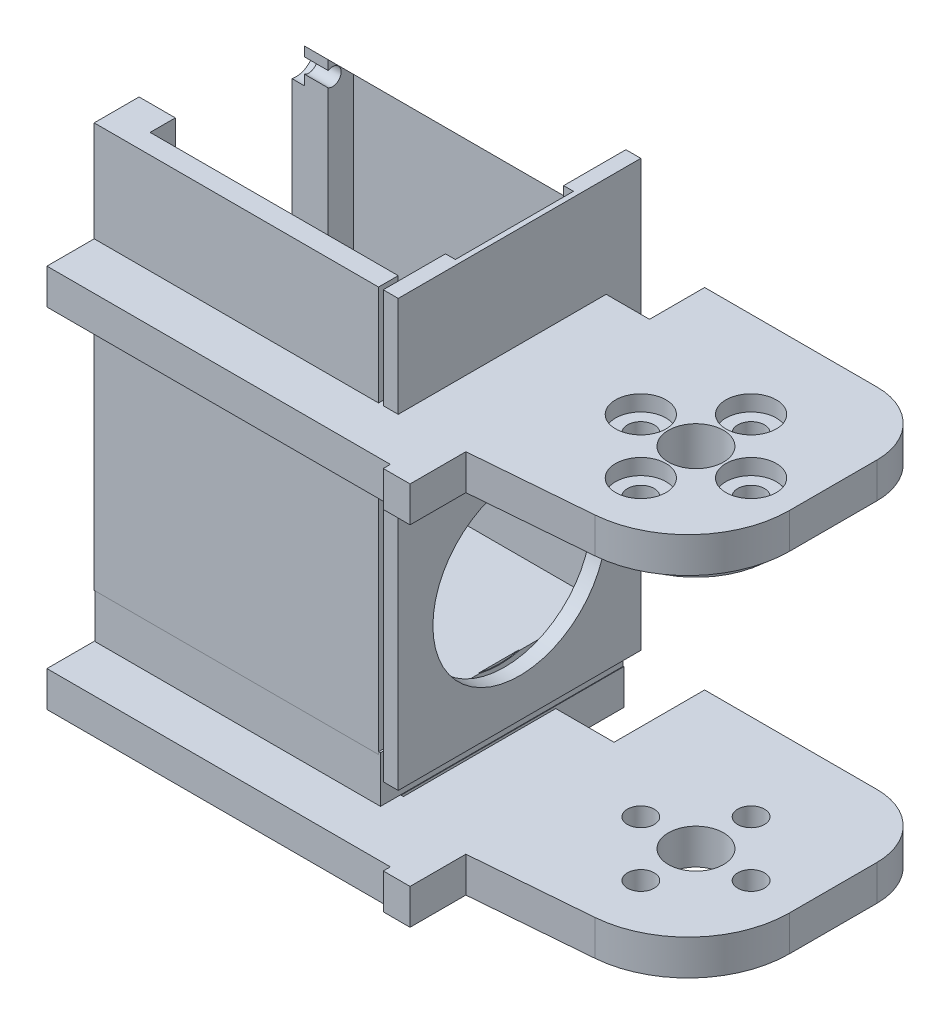
SolidWorks part; units mm, degrees
ref_plane "Front Plane" through (0, 0, 0) normal (0, 0, 1) x (1, 0, 0)
ref_plane "Top Plane" through (0, 0, 0) normal (0, 1, 0) x (1, 0, 0)
ref_plane "Right Plane" through (0, 0, 0) normal (1, 0, 0) x (0, 0, -1)
ref_plane "PY_m23_300" through (0, -23.3, 0) normal (0, 1, 0) x (1, 0, 0)
sketch "S_prism1" plane through (0, -23.3, 0) normal (0, 1, 0) x (1, 0, 0)
  line L0 (13, 10) -> (13, -1.1138)
  line L1 (1.1535, -13.9707) -> (-16.9, -15.45)
  line L2 (-16.9, -15.45) -> (-16.9, 18)
  line L3 (-16.9, 18) -> (5, 18)
  arc A0 (5, 18) -> (13, 10) centre (5.0002, 10.0002) cw
  arc A1 (13, -1.1138) -> (1.1535, -13.9707) centre (0.1, -1.1138) cw
extrude "Boss_1" add sketch "S_prism1" along normal blind 4.5
ref_plane "PY_p17_750" through (0, 17.75, 0) normal (0, 1, 0) x (1, 0, 0)
sketch "S_cyl2" plane through (0, 17.75, 0) normal (0, 1, 0) x (1, 0, 0)
  circle A0 centre (0, 0) radius 9.5
  dimension "D1_S_cyl2" = 19
extrude "Boss_2" add sketch "S_cyl2" along normal blind 3.2
ref_plane "PY_p20_950" through (0, 20.95, 0) normal (0, 1, 0) x (1, 0, 0)
sketch "S_prism3" plane through (0, 20.95, 0) normal (0, 1, 0) x (1, 0, 0)
  line L0 (13, 10) -> (13, -1.1138)
  line L1 (1.1535, -13.9707) -> (-16.9, -15.45)
  line L2 (-16.9, -15.45) -> (-16.9, 18)
  line L3 (-16.9, 18) -> (5, 18)
  arc A0 (5, 18) -> (13, 10) centre (5.0002, 10.0002) cw
  arc A1 (13, -1.1138) -> (1.1535, -13.9707) centre (0.1, -1.1138) cw
extrude "Boss_3" add sketch "S_prism3" along normal blind 4.5
sketch "S_prism4" plane through (0, -23.3, 0) normal (0, 1, 0) x (1, 0, 0)
  line L0 (-24.3, 6.5) -> (-16.8, 6.5)
  line L1 (-16.8, 6.5) -> (-16.8, -15.45)
  line L2 (-16.8, -15.45) -> (-24.3, -15.45)
  line L3 (-24.3, -15.45) -> (-24.3, 6.5)
extrude "Boss_4" add sketch "S_prism4" along normal blind 4.5
sketch "S_prism5" plane through (0, -23.3, 0) normal (0, 1, 0) x (1, 0, 0)
  line L0 (-61, -12.85) -> (-16.8, -12.85)
  line L1 (-16.8, -12.85) -> (-16.8, -21.4)
  line L2 (-16.8, -21.4) -> (-61, -21.4)
  line L3 (-61, -21.4) -> (-61, -12.85)
extrude "Boss_5" add sketch "S_prism5" along normal blind 4.5
sketch "S_prism6" plane through (0, -23.3, 0) normal (0, 1, 0) x (1, 0, 0)
  line L0 (-61, 15.45) -> (-24.6, 15.45)
  line L1 (-24.6, 15.45) -> (-24.6, -15.45)
  line L2 (-24.6, -15.45) -> (-61, -15.45)
  line L3 (-61, -15.45) -> (-61, 15.45)
extrude "Boss_6" add sketch "S_prism6" along normal blind 4.5
sketch "S_prism7" plane through (0, -23.3, 0) normal (0, 1, 0) x (1, 0, 0)
  line L0 (-17.4, -14.4) -> (-14, -14.4)
  line L1 (-14, -14.4) -> (-14, -22.3)
  line L2 (-14, -22.3) -> (-17.4, -22.3)
  line L3 (-17.4, -22.3) -> (-17.4, -14.4)
extrude "Boss_7" add sketch "S_prism7" along normal blind 4.5
sketch "S_prism8" plane through (0, 20.95, 0) normal (0, 1, 0) x (1, 0, 0)
  line L0 (-24.3, 11) -> (-16.8, 11)
  line L1 (-16.8, 11) -> (-16.8, -15.45)
  line L2 (-16.8, -15.45) -> (-24.3, -15.45)
  line L3 (-24.3, -15.45) -> (-24.3, 11)
extrude "Boss_8" add sketch "S_prism8" along normal blind 4.5
sketch "S_prism9" plane through (0, 20.95, 0) normal (0, 1, 0) x (1, 0, 0)
  line L0 (-61, -12.85) -> (-16.8, -12.85)
  line L1 (-16.8, -12.85) -> (-16.8, -21.4)
  line L2 (-16.8, -21.4) -> (-61, -21.4)
  line L3 (-61, -21.4) -> (-61, -12.85)
extrude "Boss_9" add sketch "S_prism9" along normal blind 4.5
sketch "S_prism10" plane through (0, 20.95, 0) normal (0, 1, 0) x (1, 0, 0)
  line L0 (-17.4, -14.4) -> (-14, -14.4)
  line L1 (-14, -14.4) -> (-14, -22.3)
  line L2 (-14, -22.3) -> (-17.4, -22.3)
  line L3 (-17.4, -22.3) -> (-17.4, -14.4)
extrude "Boss_10" add sketch "S_prism10" along normal blind 4.5
ref_plane "PZ_m15_400" through (0, 0, -15.4) normal (0, 0, 1) x (1, 0, 0)
sketch "S_box11" plane through (0, 0, -15.4) normal (0, 0, 1) x (1, 0, 0)
  line L0 (-61, -13.2) -> (-24.9, -13.2)
  line L1 (-24.9, -13.2) -> (-24.9, -10.7)
  line L2 (-24.9, -10.7) -> (-61, -10.7)
  line L3 (-61, -10.7) -> (-61, -13.2)
  dimension "P1" = 61
  dimension "P2" = 13.2
  dimension "P3" = 24.9
  dimension "P4" = 13.2
  dimension "P5" = 24.9
  dimension "P6" = 10.7
  dimension "P7" = 61
  dimension "P8" = 10.7
extrude "Boss_11" add sketch "S_box11" along normal blind 30.8
sketch "S_box12" plane through (0, 0, -15.4) normal (0, 0, 1) x (1, 0, 0)
  line L0 (-61, -13.2) -> (-24.9, -13.2)
  line L1 (-24.9, -13.2) -> (-24.9, 38.2)
  line L2 (-24.9, 38.2) -> (-61, 38.2)
  line L3 (-61, 38.2) -> (-61, -13.2)
  dimension "P1" = 61
  dimension "P2" = 13.2
  dimension "P3" = 24.9
  dimension "P4" = 13.2
  dimension "P5" = 24.9
  dimension "P6" = 38.2
  dimension "P7" = 61
  dimension "P8" = 38.2
extrude "Boss_12" add sketch "S_box12" along normal blind 2.5
ref_plane "PZ_p12_900" through (0, 0, 12.9) normal (0, 0, 1) x (1, 0, 0)
sketch "S_box13" plane through (0, 0, 12.9) normal (0, 0, 1) x (1, 0, 0)
  line L0 (-61, -13.2) -> (-24.9, -13.2)
  line L1 (-24.9, -13.2) -> (-24.9, 38.2)
  line L2 (-24.9, 38.2) -> (-61, 38.2)
  line L3 (-61, 38.2) -> (-61, -13.2)
  dimension "P1" = 61
  dimension "P2" = 13.2
  dimension "P3" = 24.9
  dimension "P4" = 13.2
  dimension "P5" = 24.9
  dimension "P6" = 38.2
  dimension "P7" = 61
  dimension "P8" = 38.2
extrude "Boss_13" add sketch "S_box13" along normal blind 2.5
sketch "S_box14" plane through (0, 0, -15.4) normal (0, 0, 1) x (1, 0, 0)
  line L0 (-61, -13.2) -> (-56.4, -13.2)
  line L1 (-56.4, -13.2) -> (-56.4, 38.2)
  line L2 (-56.4, 38.2) -> (-61, 38.2)
  line L3 (-61, 38.2) -> (-61, -13.2)
  dimension "P1" = 61
  dimension "P2" = 13.2
  dimension "P3" = 56.4
  dimension "P4" = 13.2
  dimension "P5" = 56.4
  dimension "P6" = 38.2
  dimension "P7" = 61
  dimension "P8" = 38.2
extrude "Boss_14" add sketch "S_box14" along normal blind 30.8
sketch "S_box15" plane through (0, 0, -15.4) normal (0, 0, 1) x (1, 0, 0)
  line L0 (-24.3, -15.9) -> (-22.4, -15.9)
  line L1 (-22.4, -15.9) -> (-22.4, 38.2)
  line L2 (-22.4, 38.2) -> (-24.3, 38.2)
  line L3 (-24.3, 38.2) -> (-24.3, -15.9)
  dimension "P1" = 24.3
  dimension "P2" = 15.9
  dimension "P3" = 22.4
  dimension "P4" = 15.9
  dimension "P5" = 22.4
  dimension "P6" = 38.2
  dimension "P7" = 24.3
  dimension "P8" = 38.2
extrude "Boss_15" add sketch "S_box15" along normal blind 30.8
ref_plane "PZ_m15_380" through (0, 0, -15.38) normal (0, 0, 1) x (1, 0, 0)
sketch "S_box16" plane through (0, 0, -15.38) normal (0, 0, 1) x (1, 0, 0)
  line L0 (-60.93, -18.9) -> (-24.67, -18.9)
  line L1 (-24.67, -18.9) -> (-24.67, -12.9)
  line L2 (-24.67, -12.9) -> (-60.93, -12.9)
  line L3 (-60.93, -12.9) -> (-60.93, -18.9)
  dimension "P1" = 60.93
  dimension "P2" = 18.9
  dimension "P3" = 24.67
  dimension "P4" = 18.9
  dimension "P5" = 24.67
  dimension "P6" = 12.9
  dimension "P7" = 60.93
  dimension "P8" = 12.9
extrude "Boss_16" add sketch "S_box16" along normal blind 30.76
ref_plane "PY_m23_400" through (0, -23.4, 0) normal (0, 1, 0) x (1, 0, 0)
sketch "S_hole17" plane through (0, -23.4, 0) normal (0, 1, 0) x (1, 0, 0)
  circle A0 centre (0, 0) radius 3.5
  dimension "D1_S_hole17" = 7
extrude "Hole_17" cut sketch "S_hole17" along normal blind 4.7
sketch "S_hole18" plane through (0, -23.4, 0) normal (0, 1, 0) x (1, 0, 0)
  circle A0 centre (7, 0) radius 1.7
  dimension "D1_S_hole18" = 3.4
  dimension "P2" = 7
extrude "Hole_18" cut sketch "S_hole18" along normal blind 4.7
sketch "S_hole19" plane through (0, -23.4, 0) normal (0, 1, 0) x (1, 0, 0)
  circle A0 centre (0, -7) radius 1.7
  dimension "D1_S_hole19" = 3.4
  dimension "P2" = 7
extrude "Hole_19" cut sketch "S_hole19" along normal blind 4.7
sketch "S_hole20" plane through (0, -23.4, 0) normal (0, 1, 0) x (1, 0, 0)
  circle A0 centre (-7, 0) radius 1.7
  dimension "D1_S_hole20" = 3.4
  dimension "P2" = 7
extrude "Hole_20" cut sketch "S_hole20" along normal blind 4.7
sketch "S_hole21" plane through (0, -23.4, 0) normal (0, 1, 0) x (1, 0, 0)
  circle A0 centre (0, 7) radius 1.7
  dimension "D1_S_hole21" = 3.4
  dimension "P2" = 7
extrude "Hole_21" cut sketch "S_hole21" along normal blind 4.7
sketch "S_hole22" plane through (0, -23.4, 0) normal (0, 1, 0) x (1, 0, 0)
  circle A0 centre (7, 0) radius 3.2
  dimension "D1_S_hole22" = 6.4
  dimension "P2" = 7
extrude "Hole_22" cut sketch "S_hole22" along normal blind 1.6
sketch "S_hole23" plane through (0, -23.4, 0) normal (0, 1, 0) x (1, 0, 0)
  circle A0 centre (0, -7) radius 3.2
  dimension "D1_S_hole23" = 6.4
  dimension "P2" = 7
extrude "Hole_23" cut sketch "S_hole23" along normal blind 1.6
sketch "S_hole24" plane through (0, -23.4, 0) normal (0, 1, 0) x (1, 0, 0)
  circle A0 centre (-7, 0) radius 3.2
  dimension "D1_S_hole24" = 6.4
  dimension "P2" = 7
extrude "Hole_24" cut sketch "S_hole24" along normal blind 1.6
sketch "S_hole25" plane through (0, -23.4, 0) normal (0, 1, 0) x (1, 0, 0)
  circle A0 centre (0, 7) radius 3.2
  dimension "D1_S_hole25" = 6.4
  dimension "P2" = 7
extrude "Hole_25" cut sketch "S_hole25" along normal blind 1.6
ref_plane "PY_p17_650" through (0, 17.65, 0) normal (0, 1, 0) x (1, 0, 0)
sketch "S_hole26" plane through (0, 17.65, 0) normal (0, 1, 0) x (1, 0, 0)
  circle A0 centre (0, 0) radius 3.5
  dimension "D1_S_hole26" = 7
extrude "Hole_26" cut sketch "S_hole26" along normal blind 7.9
sketch "S_hole27" plane through (0, 17.65, 0) normal (0, 1, 0) x (1, 0, 0)
  circle A0 centre (7, 0) radius 1.7
  dimension "D1_S_hole27" = 3.4
  dimension "P2" = 7
extrude "Hole_27" cut sketch "S_hole27" along normal blind 7.9
sketch "S_hole28" plane through (0, 17.65, 0) normal (0, 1, 0) x (1, 0, 0)
  circle A0 centre (0, -7) radius 1.7
  dimension "D1_S_hole28" = 3.4
  dimension "P2" = 7
extrude "Hole_28" cut sketch "S_hole28" along normal blind 7.9
sketch "S_hole29" plane through (0, 17.65, 0) normal (0, 1, 0) x (1, 0, 0)
  circle A0 centre (-7, 0) radius 1.7
  dimension "D1_S_hole29" = 3.4
  dimension "P2" = 7
extrude "Hole_29" cut sketch "S_hole29" along normal blind 7.9
sketch "S_hole30" plane through (0, 17.65, 0) normal (0, 1, 0) x (1, 0, 0)
  circle A0 centre (0, 7) radius 1.7
  dimension "D1_S_hole30" = 3.4
  dimension "P2" = 7
extrude "Hole_30" cut sketch "S_hole30" along normal blind 7.9
ref_plane "PY_p23_450" through (0, 23.45, 0) normal (0, 1, 0) x (1, 0, 0)
sketch "S_hole31" plane through (0, 23.45, 0) normal (0, 1, 0) x (1, 0, 0)
  circle A0 centre (7, 0) radius 3.2
  dimension "D1_S_hole31" = 6.4
  dimension "P2" = 7
extrude "Hole_31" cut sketch "S_hole31" along normal blind 2.1
sketch "S_hole32" plane through (0, 23.45, 0) normal (0, 1, 0) x (1, 0, 0)
  circle A0 centre (0, -7) radius 3.2
  dimension "D1_S_hole32" = 6.4
  dimension "P2" = 7
extrude "Hole_32" cut sketch "S_hole32" along normal blind 2.1
sketch "S_hole33" plane through (0, 23.45, 0) normal (0, 1, 0) x (1, 0, 0)
  circle A0 centre (-7, 0) radius 3.2
  dimension "D1_S_hole33" = 6.4
  dimension "P2" = 7
extrude "Hole_33" cut sketch "S_hole33" along normal blind 2.1
sketch "S_hole34" plane through (0, 23.45, 0) normal (0, 1, 0) x (1, 0, 0)
  circle A0 centre (0, 7) radius 3.2
  dimension "D1_S_hole34" = 6.4
  dimension "P2" = 7
extrude "Hole_34" cut sketch "S_hole34" along normal blind 2.1
sketch "S_cut35" plane through (0, 0, 0) normal (0, 0, 1) x (1, 0, 0)
  line L0 (-3.4, 17.65) -> (3.4, 17.65)
  line L1 (3.4, 17.65) -> (3.4, 18.65)
  line L2 (3.4, 18.65) -> (-3.4, 18.65)
  line L3 (-3.4, 18.65) -> (-3.4, 17.65)
  dimension "P1" = 3.4
  dimension "P2" = 17.65
  dimension "P3" = 3.4
  dimension "P4" = 17.65
  dimension "P5" = 3.4
  dimension "P6" = 18.65
  dimension "P7" = 3.4
  dimension "P8" = 18.65
extrude "Pocket_35" cut sketch "S_cut35" along normal blind 10
ref_plane "PX_m61_100" through (-61.1, 0, 0) normal (1, 0, 0) x (0, 0, -1)
sketch "S_hole36" plane through (-61.1, 0, 0) normal (1, 0, 0) x (0, 0, -1)
  circle A0 centre (0, 0) radius 10.5
  dimension "D1_S_hole36" = 21
extrude "Hole_36" cut sketch "S_hole36" along normal blind 4.8
ref_plane "PZ_m9_700" through (0, 0, -9.7) normal (0, 0, 1) x (1, 0, 0)
sketch "S_cut37" plane through (0, 0, -9.7) normal (0, 0, 1) x (1, 0, 0)
  line L0 (-61.1, 10.9) -> (-56.35, 10.9)
  line L1 (-56.35, 10.9) -> (-56.35, 30.4)
  line L2 (-56.35, 30.4) -> (-61.1, 30.4)
  line L3 (-61.1, 30.4) -> (-61.1, 10.9)
  dimension "P1" = 61.1
  dimension "P2" = 10.9
  dimension "P3" = 56.35
  dimension "P4" = 10.9
  dimension "P5" = 56.35
  dimension "P6" = 30.4
  dimension "P7" = 61.1
  dimension "P8" = 30.4
extrude "Pocket_37" cut sketch "S_cut37" along normal blind 19.4
sketch "S_cut38" plane through (0, 0, -9.7) normal (0, 0, 1) x (1, 0, 0)
  line L0 (-61.1, 30.4) -> (-56.35, 30.4)
  line L1 (-56.35, 30.4) -> (-56.35, 38.7)
  line L2 (-56.35, 38.7) -> (-61.1, 38.7)
  line L3 (-61.1, 38.7) -> (-61.1, 30.4)
  dimension "P1" = 61.1
  dimension "P2" = 30.4
  dimension "P3" = 56.35
  dimension "P4" = 30.4
  dimension "P5" = 56.35
  dimension "P6" = 38.7
  dimension "P7" = 61.1
  dimension "P8" = 38.7
extrude "Pocket_38" cut sketch "S_cut38" along normal blind 19.4
ref_plane "PZ_m3_500" through (0, 0, -3.5) normal (0, 0, 1) x (1, 0, 0)
sketch "S_cut39" plane through (0, 0, -3.5) normal (0, 0, 1) x (1, 0, 0)
  line L0 (-61.1, 0) -> (-56.35, 0)
  line L1 (-56.35, 0) -> (-56.35, 11)
  line L2 (-56.35, 11) -> (-61.1, 11)
  line L3 (-61.1, 11) -> (-61.1, 0)
  dimension "P1" = 61.1
  dimension "P2" = 56.35
  dimension "P3" = 56.35
  dimension "P4" = 11
  dimension "P5" = 61.1
  dimension "P6" = 11
extrude "Pocket_39" cut sketch "S_cut39" along normal blind 7
ref_plane "PZ_m15_900" through (0, 0, -15.9) normal (0, 0, 1) x (1, 0, 0)
sketch "S_cut40" plane through (0, 0, -15.9) normal (0, 0, 1) x (1, 0, 0)
  line L0 (-61.2, -10) -> (-58.3, -10)
  line L1 (-58.3, -10) -> (-58.3, 10)
  line L2 (-58.3, 10) -> (-61.2, 10)
  line L3 (-61.2, 10) -> (-61.2, -10)
  dimension "P1" = 61.2
  dimension "P2" = 10
  dimension "P3" = 58.3
  dimension "P4" = 10
  dimension "P5" = 58.3
  dimension "P6" = 10
  dimension "P7" = 61.2
  dimension "P8" = 10
extrude "Pocket_40" cut sketch "S_cut40" along normal blind 15.9
sketch "S_hole41" plane through (-61.1, 0, 0) normal (1, 0, 0) x (0, 0, -1)
  circle A0 centre (-10.25, 8.3) radius 1.1
  dimension "D1_S_hole41" = 2.2
  dimension "P2" = 10.25
  dimension "P3" = 8.3
extrude "Hole_41" cut sketch "S_hole41" along normal blind 4.8
sketch "S_hole42" plane through (-61.1, 0, 0) normal (1, 0, 0) x (0, 0, -1)
  circle A0 centre (-10.25, 8.3) radius 2.3
  dimension "D1_S_hole42" = 4.6
  dimension "P2" = 10.25
  dimension "P3" = 8.3
extrude "Hole_42" cut sketch "S_hole42" along normal blind 1.7
sketch "S_hole43" plane through (-61.1, 0, 0) normal (1, 0, 0) x (0, 0, -1)
  circle A0 centre (10.25, 32.75) radius 1.1
  dimension "D1_S_hole43" = 2.2
  dimension "P2" = 10.25
  dimension "P3" = 32.75
extrude "Hole_43" cut sketch "S_hole43" along normal blind 4.8
sketch "S_hole44" plane through (-61.1, 0, 0) normal (1, 0, 0) x (0, 0, -1)
  circle A0 centre (10.25, 32.75) radius 2.3
  dimension "D1_S_hole44" = 4.6
  dimension "P2" = 10.25
  dimension "P3" = 32.75
extrude "Hole_44" cut sketch "S_hole44" along normal blind 1.7
sketch "S_hole45" plane through (-61.1, 0, 0) normal (1, 0, 0) x (0, 0, -1)
  circle A0 centre (-10.25, 32.75) radius 1.1
  dimension "D1_S_hole45" = 2.2
  dimension "P2" = 10.25
  dimension "P3" = 32.75
extrude "Hole_45" cut sketch "S_hole45" along normal blind 4.8
sketch "S_hole46" plane through (-61.1, 0, 0) normal (1, 0, 0) x (0, 0, -1)
  circle A0 centre (-10.25, 32.75) radius 2.3
  dimension "D1_S_hole46" = 4.6
  dimension "P2" = 10.25
  dimension "P3" = 32.75
extrude "Hole_46" cut sketch "S_hole46" along normal blind 1.7
ref_plane "PX_m25_000" through (-25, 0, 0) normal (1, 0, 0) x (0, 0, -1)
sketch "S_hole47" plane through (-25, 0, 0) normal (1, 0, 0) x (0, 0, -1)
  circle A0 centre (0, 0) radius 11
  dimension "D1_S_hole47" = 22
extrude "Hole_47" cut sketch "S_hole47" along normal blind 2.7
ref_plane "PZ_m7_500" through (0, 0, -7.5) normal (0, 0, 1) x (1, 0, 0)
sketch "S_cut48" plane through (0, 0, -7.5) normal (0, 0, 1) x (1, 0, 0)
  line L0 (-24.9, 8.1) -> (-23.05, 8.1)
  line L1 (-23.05, 8.1) -> (-23.05, 38.7)
  line L2 (-23.05, 38.7) -> (-24.9, 38.7)
  line L3 (-24.9, 38.7) -> (-24.9, 8.1)
  dimension "P1" = 24.9
  dimension "P2" = 8.1
  dimension "P3" = 23.05
  dimension "P4" = 8.1
  dimension "P5" = 23.05
  dimension "P6" = 38.7
  dimension "P7" = 24.9
  dimension "P8" = 38.7
extrude "Pocket_48" cut sketch "S_cut48" along normal blind 15
sketch "S_pcut49" plane through (-61.1, 0, 0) normal (1, 0, 0) x (0, 0, -1)
  line L0 (16, 38.8) -> (16, 28.6)
  line L1 (16, 28.6) -> (5.8, 38.8)
  line L2 (5.8, 38.8) -> (16, 38.8)
extrude "Cut_49" cut sketch "S_pcut49" along normal blind 36.3
equation "\"plate_t\" = 3"
equation "\"clearance\" = 0.5"
